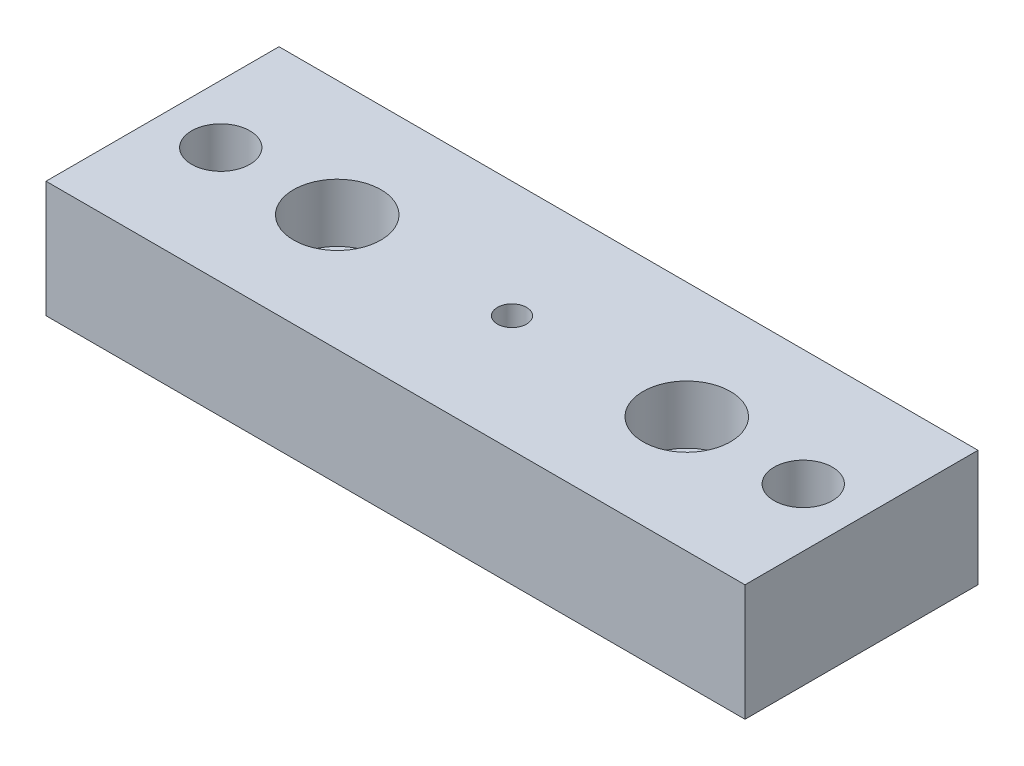
SolidWorks part; units mm, degrees
ref_plane "Alzado" through (0, 0, 0) normal (0, 0, 1) x (1, 0, 0)
ref_plane "Planta" through (0, 0, 0) normal (0, 1, 0) x (1, 0, 0)
ref_plane "Vista lateral" through (0, 0, 0) normal (1, 0, 0) x (0, 0, -1)
sketch "Croquis1" plane through (0, 0, 0) normal (0, 1, 0) x (1, 0, 0)
  line L1 (60, -20) -> (-60, -20)
  line L2 (60, -20) -> (60, 20)
  line L3 (60, 20) -> (-60, 20)
  line L4 (-60, -20) -> (-60, 20)
  line L5 (60, -20) -> (-60, 20) construction
  line L6 (60, 20) -> (-60, -20) construction
  point P0 (0, 0)
  dimension "D1" = 40
  dimension "D2" = 120
extrude "Extruir1" add sketch "Croquis1" along normal blind 20
sketch "Croquis2" plane through (0, 20, 0) normal (0, 1, 0) x (1, 0, 0)
  line L0 (0, 0) -> (-60, 0) construction
  line L1 (-60, 20) -> (-60, -20) construction
  line L2 (0, 0) -> (0, 20) construction
  line L3 (60, 20) -> (-60, 20) construction
  circle A0 centre (-50, 0) radius 5
  circle A1 centre (50, 0) radius 5
  dimension "D1" = 10
  dimension "D2" = 10
extrude "Extruir2" cut sketch "Croquis2" against normal through all
sketch "Croquis4" plane through (0, 20, 0) normal (0, 1, 0) x (1, 0, 0)
  line L0 (0, 0) -> (-60, 0) construction
  line L1 (-60, 20) -> (-60, -20) construction
  line L2 (0, 0) -> (0, 20) construction
  line L3 (60, 20) -> (-60, 20) construction
  circle A0 centre (-30, 0) radius 7.5
  circle A1 centre (30, 0) radius 7.5
  circle A2 centre (0, 0) radius 2.5
  dimension "D1" = 30
  dimension "D2" = 15
  dimension "D3" = 5
extrude "Extruir3" cut sketch "Croquis4" against normal blind 10
